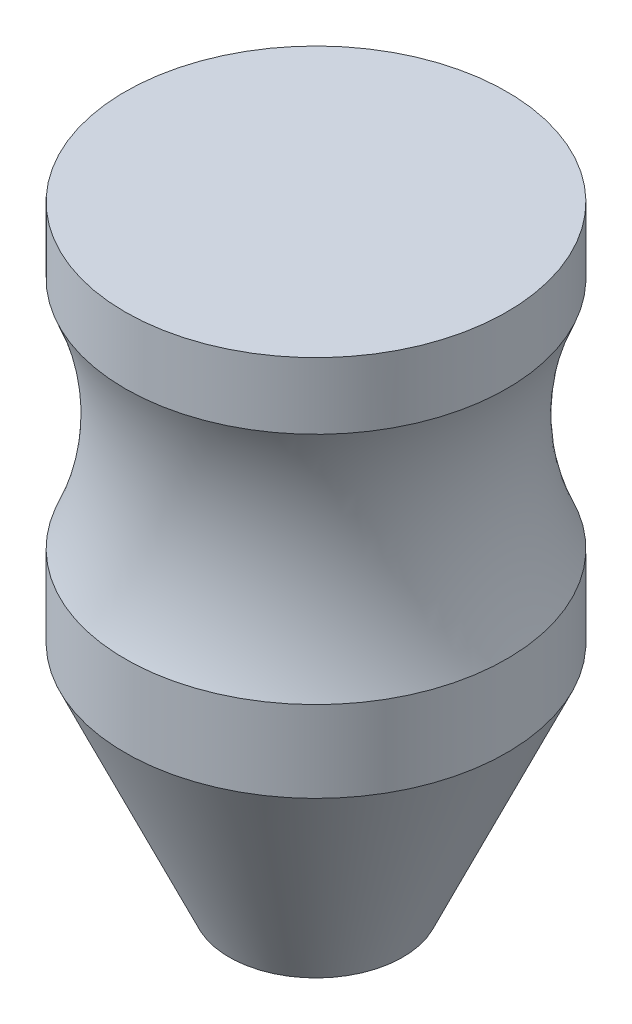
SolidWorks part; units mm, degrees
ref_plane "Front Plane" through (0, 0, 0) normal (0, 0, 1) x (1, 0, 0)
ref_plane "Top Plane" through (0, 0, 0) normal (0, 1, 0) x (1, 0, 0)
ref_plane "Right Plane" through (0, 0, 0) normal (1, 0, 0) x (0, 0, -1)
sketch "Sketch1" plane through (0, 0, 0) normal (0, 1, 0) x (1, 0, 0)
  circle A0 centre (0, 0) radius 25
  dimension "D1" = 50
extrude "Boss-Extrude1" add sketch "Sketch1" along normal blind 50 and the other way blind 30
sketch "Sketch3" plane through (0, 0, 0) normal (0, 0, 1) x (1, 0, 0)
  line L0 (25, 0) -> (11.3803, -30)
  line L1 (25, -30) -> (25, 50) construction
  line L2 (-25, -30) -> (25, -30) construction
  line L3 (11.3803, -30) -> (25, -30)
  line L4 (25, -30) -> (25, 0)
  point P8 (11.3803, -30)
revolve "Cut-Revolve1" cut sketch "Sketch3" angle 360 about axis through (0, -30, 0) along (0, 1, 0)
sketch "Sketch4" plane through (0, 0, 0) normal (0, 0, 1) x (1, 0, 0)
  line L0 (25, 0) -> (25, 50) construction
  line L1 (25, 41.3015) -> (25, 10.6432)
  arc A0 (25, 10.6432) -> (25, 41.3015) centre (59.6544, 25.9723) cw
revolve "Cut-Revolve2" cut sketch "Sketch4" angle 360 about axis through (0, -30, 0) along (0, 1, 0)
